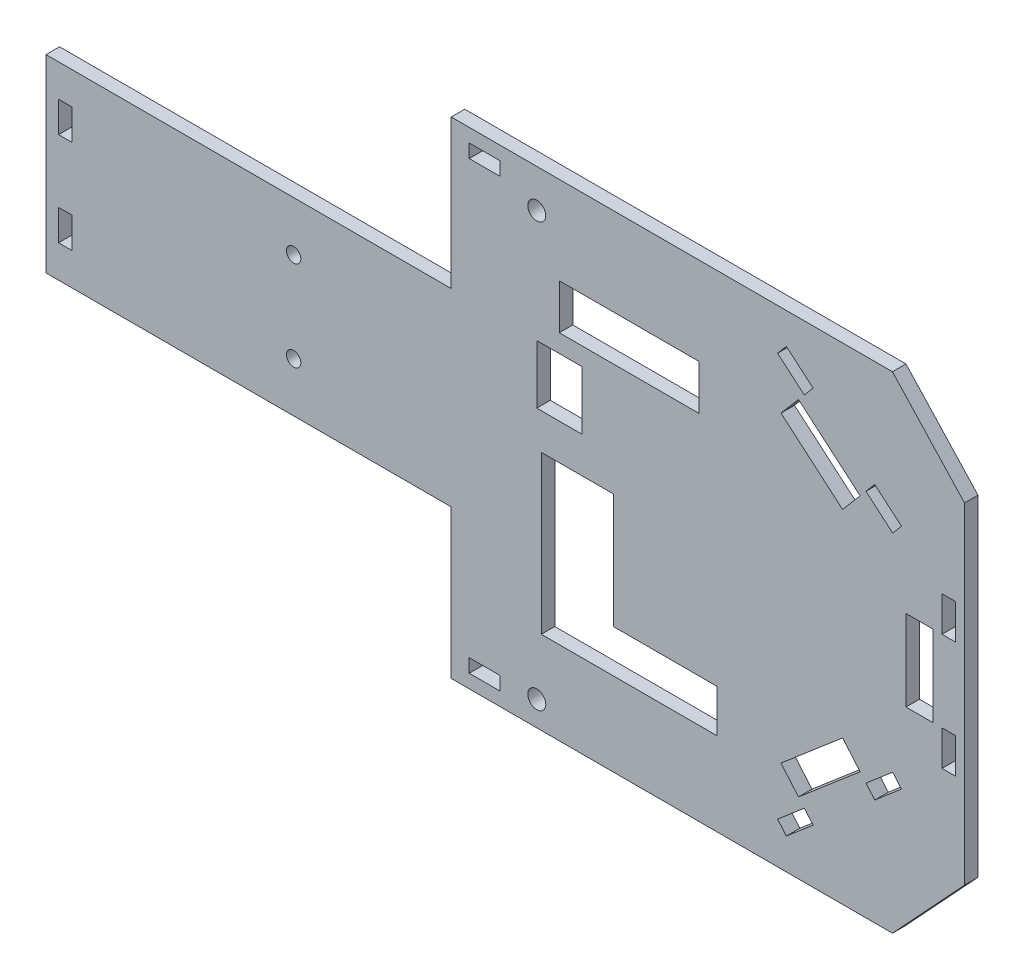
SolidWorks part; units mm, degrees
ref_plane "Plano frontal" through (0, 0, 0) normal (0, 0, 1) x (1, 0, 0)
ref_plane "Plano superior" through (0, 0, 0) normal (0, 1, 0) x (1, 0, 0)
ref_plane "Plano direito" through (0, 0, 0) normal (1, 0, 0) x (0, 0, -1)
sketch "Esboço1" plane through (0, 0, 0) normal (0, 0, 1) x (1, 0, 0)
  line L0 (0, 54) -> (204, 54) construction
  line L5 (0, 33) -> (0, 75)
  line L6 (0, 75) -> (90, 75)
  line L7 (90, 75) -> (90, 108)
  line L8 (90, 108) -> (188, 108)
  line L9 (188, 108) -> (204, 90.7565)
  line L10 (204, 90.7565) -> (204, 17.2435)
  line L11 (188, 0) -> (204, 17.2435)
  line L12 (90, 0) -> (188, 0)
  line L13 (90, 33) -> (90, 0)
  line L14 (0, 33) -> (90, 33)
  dimension "D1" = 108
  dimension "D2" = 42
  dimension "D3" = 98
  dimension "D4" = 114
  dimension "D5" = 204
extrude "Ressalto-extrusão1" add sketch "Esboço1" along normal blind 3
sketch "Esboço2" plane through (0, 0, 3) normal (0, 0, 1) x (1, 0, 0)
  line L0 (90, 0) -> (188, 0) construction
  line L1 (110, 18.5) -> (126, 18.5)
  line L2 (110, 18.5) -> (110, 53.5)
  line L3 (110, 53.5) -> (126, 53.5)
  line L4 (126, 18.5) -> (126, 53.5)
  line L5 (90, 33) -> (90, 0) construction
  line L7 (126, 18.5) -> (149, 18.5)
  line L8 (126, 18.5) -> (126, 28)
  line L9 (126, 28) -> (149, 28)
  line L10 (149, 18.5) -> (149, 28)
  line L11 (109, 61.5) -> (119, 61.5)
  line L12 (109, 61.5) -> (109, 74.5)
  line L13 (109, 74.5) -> (119, 74.5)
  line L14 (119, 61.5) -> (119, 74.5)
  line L15 (114, 88.5) -> (145, 88.5)
  line L16 (114, 88.5) -> (114, 78.5)
  line L17 (114, 78.5) -> (145, 78.5)
  line L18 (145, 88.5) -> (145, 78.5)
  line L19 (90, 108) -> (90, 75) construction
  circle A0 centre (109, 5.5) radius 2
  circle A1 centre (109, 99.5) radius 2
  dimension "D13" = 4
  dimension "D14" = 4
  dimension "D15" = 94
  dimension "D16" = 5.5
  dimension "D17" = 19
  dimension "D18" = 19
  dimension "D19" = 24
  dimension "D1" = 35
  dimension "D2" = 16
  dimension "D3" = 18.5
  dimension "D4" = 20
  dimension "D5" = 23
  dimension "D6" = 9.5
  dimension "D7" = 8
  dimension "D8" = 13
  dimension "D9" = 10
  dimension "D10" = 4
  dimension "D11" = 10
  dimension "D12" = 55
  dimension "D20" = 19
extrude "Corte-extrusão1" cut sketch "Esboço2" against normal through all contours L18 L15 L16 L17 | L1 L4 L3 L2 | L11 L14 L13 L12 | L7 L10 L9 L4 | A0 | A1
sketch "Esboço3" plane through (0, 0, 3) normal (0, 0, 1) x (1, 0, 0)
  line L0 (164.4373, 6.9115) -> (170.3715, 11.9736)
  line L1 (162.4903, 9.1939) -> (168.4245, 14.256)
  line L2 (199, 45) -> (202, 45)
  line L3 (204, 17.2435) -> (204, 90.7565) construction
  line L4 (162.4903, 9.1939) -> (164.4373, 6.9115)
  line L5 (190, 28.7176) -> (188.053, 31)
  line L6 (182.1188, 25.9379) -> (184.0658, 23.6555)
  line L7 (168.4245, 14.256) -> (170.3715, 11.9736)
  line L8 (182.1188, 25.9379) -> (188.053, 31)
  line L9 (184.0658, 23.6555) -> (190, 28.7176)
  line L10 (90, 0) -> (188, 0) construction
  line L11 (204, 54) -> (0, 54) construction
  line L12 (0, 75) -> (0, 33) construction
  line L13 (184.0658, 84.3445) -> (190, 79.2824)
  line L14 (182.1188, 82.0621) -> (184.0658, 84.3445)
  line L15 (182.1188, 82.0621) -> (188.053, 77)
  line L16 (190, 79.2824) -> (188.053, 77)
  line L17 (162.4903, 98.8061) -> (164.4373, 101.0885)
  line L18 (162.4903, 98.8061) -> (168.4245, 93.744)
  line L19 (168.4245, 93.744) -> (170.3715, 96.0264)
  line L20 (164.4373, 101.0885) -> (170.3715, 96.0264)
  line L21 (167.1265, 15.7776) -> (180.8208, 27.4594)
  line L22 (202, 37.2) -> (199, 37.2)
  line L23 (202, 37.2) -> (202, 45)
  line L24 (202, 70.8) -> (199, 70.8)
  line L25 (199, 37.2) -> (199, 45)
  line L26 (90, 75) -> (0, 75) construction
  line L27 (197, 45) -> (191, 45)
  line L28 (180.8208, 27.4594) -> (176.9269, 32.0242)
  line L29 (176.9269, 32.0242) -> (163.2326, 20.3424)
  line L30 (163.2326, 20.3424) -> (167.1265, 15.7776)
  line L31 (176.9269, 75.9758) -> (163.2326, 87.6576)
  line L32 (180.8208, 80.5406) -> (176.9269, 75.9758)
  line L33 (167.1265, 92.2224) -> (180.8208, 80.5406)
  line L34 (163.2326, 87.6576) -> (167.1265, 92.2224)
  line L35 (199, 63) -> (202, 63)
  line L36 (197, 45) -> (197, 63)
  line L37 (197, 63) -> (191, 63)
  line L38 (199, 63) -> (199, 70.8)
  line L39 (202, 63) -> (202, 70.8)
  line L40 (191, 45) -> (191, 63)
  line L41 (197, 45) -> (191, 63) construction
  line L42 (197, 63) -> (191, 45) construction
  line L43 (2.8, 40.2) -> (5.8, 40.2)
  line L44 (2.8, 40.2) -> (2.8, 47)
  line L45 (2.8, 47) -> (5.8, 47)
  line L46 (5.8, 40.2) -> (5.8, 47)
  line L47 (2.8, 40.2) -> (5.8, 47) construction
  line L48 (2.8, 47) -> (5.8, 40.2) construction
  line L49 (0, 33) -> (90, 33) construction
  line L50 (2.8, 61) -> (5.8, 61)
  line L51 (5.8, 67.8) -> (5.8, 61)
  line L52 (2.8, 67.8) -> (5.8, 67.8)
  line L53 (2.8, 67.8) -> (2.8, 61)
  point P6 (194, 54)
  point P25 (186.25, 54)
  point P46 (4.3, 43.6)
  dimension "D3" = 3
  dimension "D4" = 7.8
  dimension "D5" = 31
  dimension "D6" = 7.8
  dimension "D7" = 14
  dimension "D8" = 7.8
  dimension "D9" = 7.8
  dimension "D10" = 2
  dimension "D11" = 2
  dimension "D12" = 6
  dimension "D13" = 18
  dimension "D15" = 3
  dimension "D16" = 0
  dimension "D17" = 0
  dimension "D18" = 6
  dimension "D19" = 2
  dimension "D20" = 18
  dimension "D21" = 6.8
  dimension "D22" = 42
  dimension "D23" = 7
  dimension "D24" = 2.8
  dimension "D25" = 3
  dimension "D26" = 18
  dimension "D27" = 18
extrude "Corte-extrusão2" cut sketch "Esboço3" against normal blind 10
sketch "Esboço4" plane through (0, 0, 3) normal (0, 0, 1) x (1, 0, 0)
  line L0 (204, 54) -> (0, 54) construction
  line L1 (204, 17.2435) -> (204, 90.7565) construction
  line L2 (0, 75) -> (0, 33) construction
  line L3 (90, 108) -> (90, 75) construction
  line L4 (94, 105) -> (100.8, 105)
  line L5 (94, 105) -> (94, 102)
  line L6 (94, 102) -> (100.8, 102)
  line L7 (100.8, 105) -> (100.8, 102)
  line L8 (188, 108) -> (90, 108) construction
  line L9 (94, 6) -> (100.8, 6)
  line L10 (100.8, 3) -> (100.8, 6)
  line L11 (94, 3) -> (100.8, 3)
  line L12 (94, 3) -> (94, 6)
  dimension "D1" = 6.8
  dimension "D2" = 3
  dimension "D3" = 4
  dimension "D4" = 3
extrude "Corte-extrusão3" cut sketch "Esboço4" against normal blind 10
sketch "Esboço6" plane through (0, 0, 3) normal (0, 0, 1) x (1, 0, 0)
  line L0 (0, 75) -> (0, 33) construction
  line L1 (0, 54) -> (204, 54) construction
  line L2 (204, 17.2435) -> (204, 90.7565) construction
  line L3 (90, 33) -> (90, 0) construction
  circle A0 centre (55, 44) radius 1.6
  circle A1 centre (55, 64) radius 1.6
  dimension "D1" = 3.2
  dimension "D2" = 10
  dimension "D3" = 35
extrude "Corte-extrusão5" cut sketch "Esboço6" against normal blind 10
